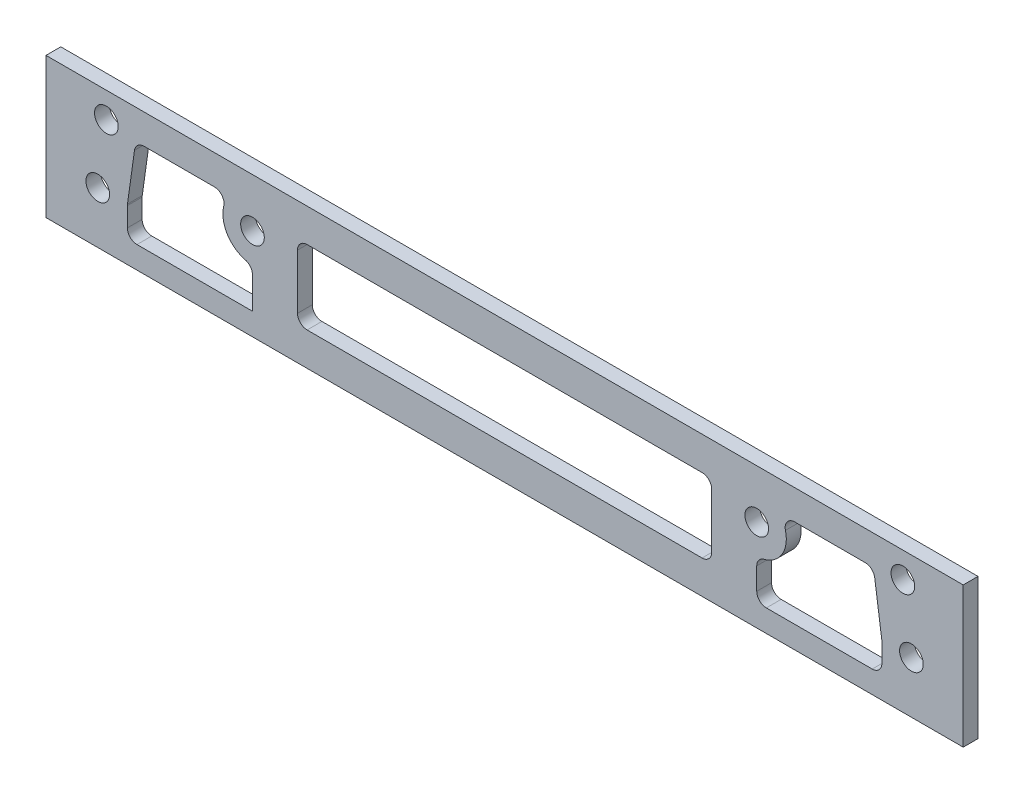
SolidWorks part; units mm, degrees
material "环氧树脂FR-4"
ref_plane "前视基准面" through (0, 0, 0) normal (0, 0, 1) x (1, 0, 0)
ref_plane "上视基准面" through (0, 0, 0) normal (0, 1, 0) x (1, 0, 0)
ref_plane "右视基准面" through (0, 0, 0) normal (1, 0, 0) x (0, 0, -1)
sketch "草图1" plane through (0, 0, 0) normal (0, 0, 1) x (1, 0, 0)
  line L1 (62, -9.5) -> (-62, -9.5)
  line L2 (62, -9.5) -> (62, 9.5)
  line L3 (62, 9.5) -> (-62, 9.5)
  line L4 (-62, -9.5) -> (-62, 9.5)
  line L5 (62, -9.5) -> (-62, 9.5) construction
  line L6 (62, 9.5) -> (-62, -9.5) construction
  point P0 (0, 0)
  dimension "D1" = 19
  dimension "D2" = 124
extrude "凸台-拉伸1" add sketch "草图1" along normal blind 2
sketch "草图3" plane through (0, 0, 2) normal (0, 0, 1) x (1, 0, 0)
  line L0 (-62, -9.5) -> (62, -9.5) construction
  line L1 (-62, 9.5) -> (-62, -9.5) construction
  line L3 (0, 0) -> (0, -9.5) construction
  circle A0 centre (-55, -2.5) radius 1.6
  circle A2 centre (55, -2.5) radius 1.6
  dimension "D3" = 3.2
  dimension "D1" = 7
  dimension "D2" = 7
extrude "切除-拉伸2" cut sketch "草图3" against normal through all
sketch "草图4" plane through (0, 0, 2) normal (0, 0, 1) x (1, 0, 0)
  line L0 (-53.84, 6.04) -> (-34.0862, 2.9113) construction
  line L1 (-62, -9.5) -> (62, -9.5) construction
  line L2 (0, 0) -> (0, -9.5) construction
  line L3 (-62, -9.5) -> (62, -9.5) construction
  circle A0 centre (-53.84, 6.04) radius 1.6
  circle A1 centre (-34.0862, 2.9113) radius 1.6
  circle A2 centre (-55, -2.5) radius 1.6 construction
  circle A3 centre (34.0862, 2.9113) radius 1.6
  circle A4 centre (53.84, 6.04) radius 1.6
  dimension "D2" = 8.54
  dimension "D3" = 3.2
  dimension "D1" = 1.16
  dimension "D4" = 9
  dimension "D5" = 20
extrude "切除-拉伸3" cut sketch "草图4" against normal through all
sketch "草图5" plane through (0, 0, 2) normal (0, 0, 1) x (1, 0, 0)
  line L0 (-51, -2.5) -> (-49.8789, 5.4837)
  line L1 (28, -5) -> (-28, -5)
  line L2 (28, -5) -> (28, 5)
  line L3 (28, 5) -> (-28, 5)
  line L4 (-28, -5) -> (-28, 5)
  line L5 (28, -5) -> (-28, 5) construction
  line L6 (28, 5) -> (-28, -5) construction
  line L7 (-49.8789, 5.4837) -> (-37.1493, 5.4837)
  line L8 (-51, -2.5) -> (-51, -6.5)
  line L9 (-51, -6.5) -> (-34.0862, -6.5)
  line L10 (-34.0862, -6.5) -> (-34.0862, -1.0887)
  line L11 (-62, -9.5) -> (62, -9.5) construction
  line L12 (0, 9.5) -> (0, -9.5) construction
  line L13 (62, 9.5) -> (-62, 9.5) construction
  line L14 (34.0862, -6.5) -> (34.0862, -1.0887)
  line L15 (51, -6.5) -> (34.0862, -6.5)
  line L16 (51, -2.5) -> (51, -6.5)
  line L17 (49.8789, 5.4837) -> (37.1493, 5.4837)
  line L18 (51, -2.5) -> (49.8789, 5.4837)
  circle A0 centre (-53.84, 6.04) radius 4
  circle A1 centre (-55, -2.5) radius 4
  circle A2 centre (-34.0862, 2.9113) radius 4
  circle A3 centre (34.0862, 2.9113) radius 4
  circle A4 centre (55, -2.5) radius 4
  circle A5 centre (53.84, 6.04) radius 4
  point P0 (0, 0)
  dimension "D1" = 8
  dimension "D2" = 3
  dimension "D3" = 56
  dimension "D4" = 10
extrude "切除-拉伸4" cut sketch "草图5" against normal through all contours A2 L7 L0 L8 L9 L10 | L4 L1 L2 L3 | L17 A3 L14 L15 L16 L18
fillet "圆角1" radius 1.3 15 edges at (28, 5, 1) (28, -5, 1) (34.0862, -6.5, 1) (51, -6.5, 1) (51, -2.5, 1) (49.8789, 5.4837, 1) (34.0862, -1.0887, 1) (37.1493, 5.4837, 1) (-28, 5, 1) (-28, -5, 1) (-51, -2.5, 1) (-51, -6.5, 1) (-49.8789, 5.4837, 1) (-37.1493, 5.4837, 1) (-34.0862, -1.0887, 1)
